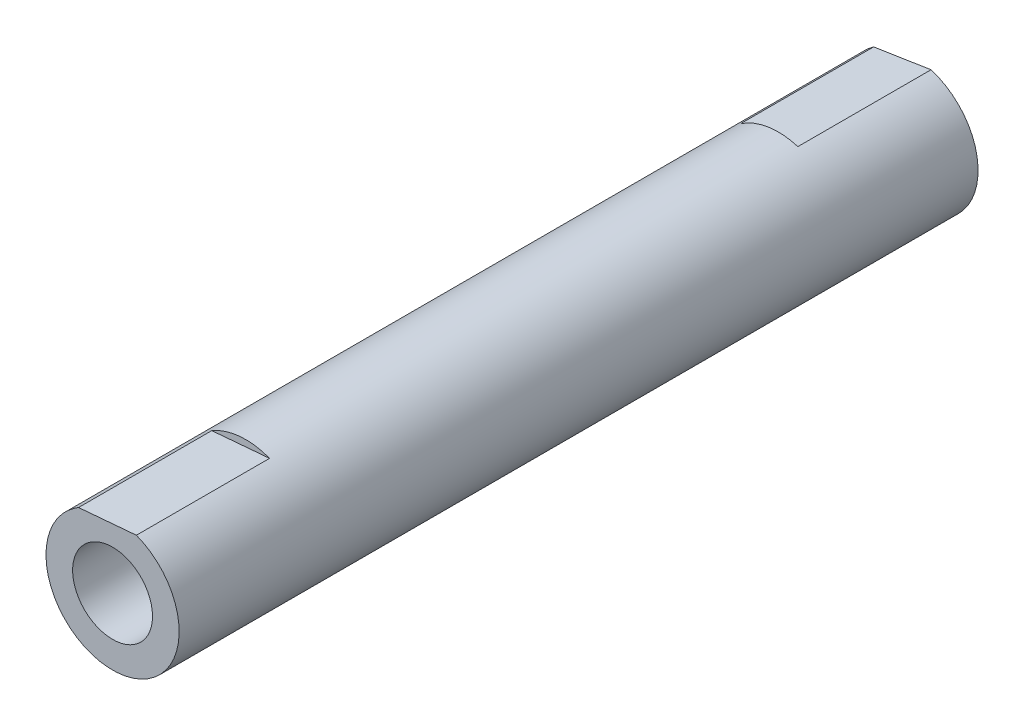
SolidWorks part; units mm, degrees
ref_plane "Front Plane" through (0, 0, 0) normal (0, 0, 1) x (1, 0, 0)
ref_plane "Top Plane" through (0, 0, 0) normal (0, 1, 0) x (1, 0, 0)
ref_plane "Right Plane" through (0, 0, 0) normal (1, 0, 0) x (0, 0, -1)
sketch "Sketch1" plane through (0, 0, 0) normal (0, 0, 1) x (1, 0, 0)
  circle A0 centre (0, 0) radius 5
  circle A1 centre (0, 0) radius 3
  dimension "D1" = 10
  dimension "D2" = 6
extrude "Boss-Extrude1" add sketch "Sketch1" along normal mid plane 60
sketch "Sketch2" plane through (0, 0, 30) normal (0, 0, 1) x (1, 0, 0)
  line L0 (-2.5529, 4.2992) -> (1.7903, 4.6685)
  circle A0 centre (0, 0) radius 5 construction
  arc A1 (1.7903, 4.6685) -> (-2.5529, 4.2992) centre (0, 0) ccw
  dimension "D1" = 4.5
extrude "Cut-Extrude1" cut sketch "Sketch2" against normal blind 10
sketch "Sketch3" plane through (0, 0, -30) normal (0, 0, -1) x (-1, 0, 0)
  line L0 (-1.4662, 4.7802) -> (2.8415, 4.1141)
  circle A0 centre (0, 0) radius 5 construction
  arc A1 (2.8415, 4.1141) -> (-1.4662, 4.7802) centre (0, 0) ccw
  dimension "D1" = 4.5
extrude "Cut-Extrude2" cut sketch "Sketch3" against normal blind 10 contours L0 A1
